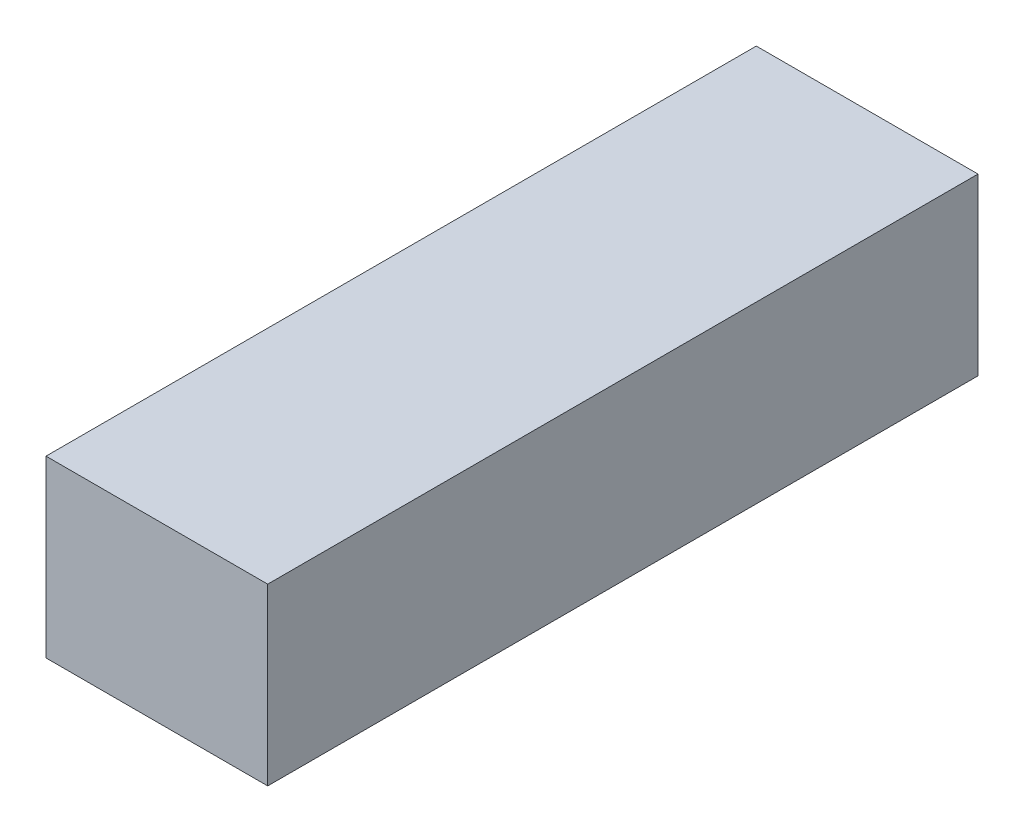
SolidWorks part; units mm, degrees
ref_plane "Front Plane" through (0, 0, 0) normal (0, 0, 1) x (1, 0, 0)
ref_plane "Top Plane" through (0, 0, 0) normal (0, 1, 0) x (1, 0, 0)
ref_plane "Right Plane" through (0, 0, 0) normal (1, 0, 0) x (0, 0, -1)
sketch "Sketch1" plane through (0, 0, 0) normal (0, 1, 0) x (1, 0, 0)
  line L5 (0, 0) -> (31.7118, 0)
  line L6 (0, 0) -> (0, 101.6)
  line L7 (0, 101.6) -> (31.7118, 101.6)
  line L8 (31.7118, 0) -> (31.7118, 101.6)
  dimension "D1" = 101.6
extrude "Boss-Extrude1" add sketch "Sketch1" along normal blind 25
